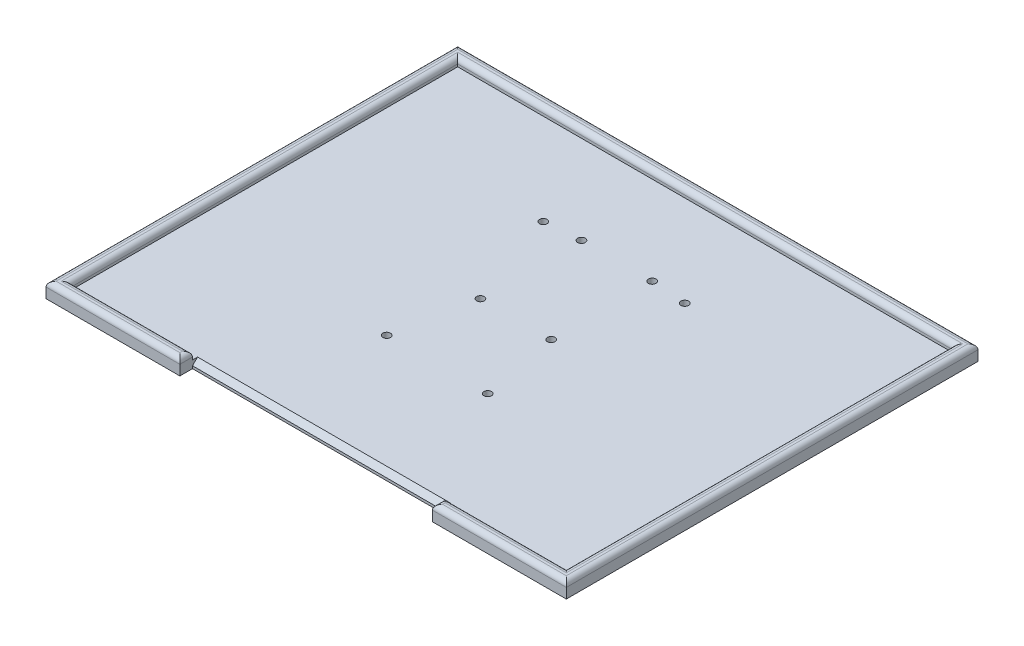
SolidWorks part; units mm, degrees
material "ABS"
ref_plane "Alzado" through (0, 0, 0) normal (0, 0, 1) x (1, 0, 0)
ref_plane "Planta" through (0, 0, 0) normal (0, 1, 0) x (1, 0, 0)
ref_plane "Vista lateral" through (0, 0, 0) normal (1, 0, 0) x (0, 0, -1)
sketch "Croquis1" plane through (0, 0, 0) normal (0, 1, 0) x (1, 0, 0)
  line L1 (0, 0) -> (206, 0)
  line L2 (0, 0) -> (0, 163)
  line L3 (0, 163) -> (206, 163)
  line L4 (206, 0) -> (206, 163)
  dimension "D1" = 163
  dimension "D2" = 206
extrude "Saliente-Extruir1" add sketch "Croquis1" along normal blind 3
sketch "Croquis2" plane through (0, 3, 0) normal (0, 1, 0) x (1, 0, 0)
  line L8 (0, 0) -> (206, 0) construction
  line L9 (0, 163) -> (5, 163)
  line L12 (0, 163) -> (0, 0)
  line L13 (0, 0) -> (5, 0)
  line L14 (5, 163) -> (5, 0)
  line L15 (206, 0) -> (206, 163) construction
  line L16 (0, 163) -> (206, 163)
  line L17 (0, 163) -> (0, 158)
  line L18 (0, 158) -> (206, 158)
  line L19 (206, 163) -> (206, 158)
  line L21 (0, 0) -> (206, 0)
  line L22 (0, 0) -> (0, 5)
  line L23 (0, 5) -> (206, 5)
  line L24 (206, 0) -> (206, 5)
  line L25 (206, 163) -> (201, 163)
  line L26 (206, 163) -> (206, 0)
  line L27 (206, 0) -> (201, 0)
  line L28 (201, 163) -> (201, 0)
  dimension "D1" = 5
  dimension "D2" = 5
  dimension "D3" = 5
  dimension "D4" = 5
extrude "Saliente-Extruir2" add sketch "Croquis2" along normal blind 3 contours L12 L9 L14 L13 | L26 L25 L28 L27 | L17 L16 L19 L18 | L22 L21 L24 L23
sketch "Croquis3" plane through (0, 6, 0) normal (0, 1, 0) x (1, 0, 0)
  line L0 (0, 0) -> (206, 0) construction
  line L1 (53, 0) -> (153, 0)
  line L2 (53, 0) -> (53, 5)
  line L3 (53, 5) -> (153, 5)
  line L4 (153, 0) -> (153, 5)
  line L5 (0, 163) -> (0, 0) construction
  dimension "D1" = 100
  dimension "D2" = 53
  dimension "D3" = 5
extrude "Cortar-Extruir1" cut sketch "Croquis3" against normal blind 10
fillet "Redondeo2" radius 2 12 edges at (0, 6, -81.5) (103, 6, -163) (206, 6, -81.5) (179.5, 6, 0) (153, 6, -2.5) (177, 6, -5) (201, 6, -81.5) (103, 6, -158) (5, 6, -81.5) (29, 6, -5) (53, 6, -2.5) (26.5, 6, 0)
chamfer "Chaflán1" distance 2 angle 45 1 edges at (103, 3, -5)
sketch "Croquis4" plane through (0, 3, 0) normal (0, 1, 0) x (1, 0, 0)
  line L0 (103, 158) -> (103, 7) construction
  line L1 (5, 158) -> (201, 158) construction
  line L2 (53, 7) -> (153, 7) construction
  line L3 (201, 81.5) -> (5, 81.5)
  line L4 (201, 158) -> (201, 5) construction
  line L5 (5, 158) -> (5, 5) construction
  circle A0 centre (75, 121.8803) radius 1.5
  circle A1 centre (131, 121.8803) radius 1.5
  circle A2 centre (123, 51.8803) radius 1.5
  circle A3 centre (83, 51.8803) radius 1.5
  dimension "D1" = 3
  dimension "D2" = 70
  dimension "D3" = 56
  dimension "D4" = 8
  dimension "D6" = 20
  dimension "D7" = 8
extrude "Cortar-Extruir3" cut sketch "Croquis4" against normal blind 10 contours A2 | A3 | A0 | A1
sketch "Croquis5" plane through (0, 3, 0) normal (0, 1, 0) x (1, 0, 0)
  line L2 (0, 163) -> (206, 163) construction
  circle A0 centre (89, 123) radius 1.5
  circle A1 centre (117, 123) radius 1.5
  circle A2 centre (89, 83) radius 1.5
  circle A3 centre (117, 83) radius 1.5
  point P8 (0, 0)
  point P9 (0, 0)
  point P10 (0, 0)
  point P11 (0, 0)
  dimension "D1" = 3
  dimension "D2" = 28
  dimension "D3" = 40
  dimension "D4" = 89
  dimension "D5" = 40
extrude "Cortar-Extruir4" cut sketch "Croquis5" against normal blind 10
